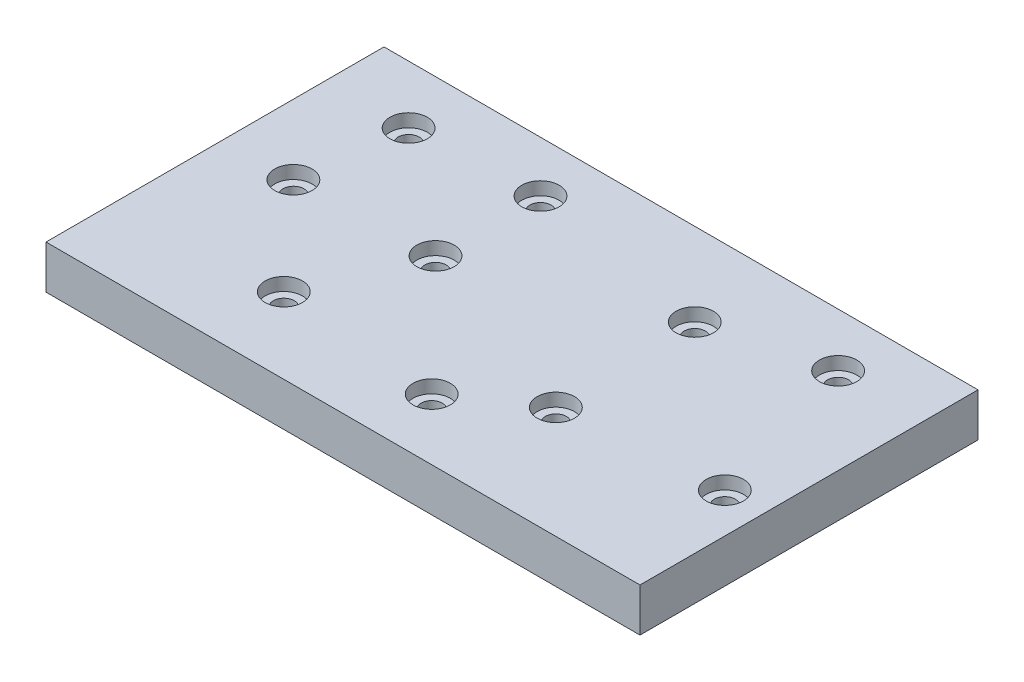
SolidWorks part; units mm, degrees
ref_plane "Front Plane" through (0, 0, 0) normal (0, 0, 1) x (1, 0, 0)
ref_plane "Top Plane" through (0, 0, 0) normal (0, 1, 0) x (1, 0, 0)
ref_plane "Right Plane" through (0, 0, 0) normal (1, 0, 0) x (0, 0, -1)
sketch "Sketch1" plane through (0, 0, 0) normal (0, 1, 0) x (1, 0, 0)
  line L1 (-68.3555, 38.8973) -> (68.3555, 38.8973)
  line L2 (-68.3555, 38.8973) -> (-68.3555, -38.8973)
  line L3 (-68.3555, -38.8973) -> (68.3555, -38.8973)
  line L4 (68.3555, 38.8973) -> (68.3555, -38.8973)
  point P0 (0, 0)
extrude "Boss-Extrude1" add sketch "Sketch1" along normal blind 10
sketch "Sketch2" plane through (0, 10, 0) normal (0, 1, 0) x (1, 0, 0)
  circle A0 centre (-49.3531, 25.5605) radius 2.4163
extrude "Cut-Extrude1" cut sketch "Sketch2" against normal blind 10
sketch "Sketch3" plane through (0, 10, 0) normal (0, 1, 0) x (1, 0, 0)
  circle A0 centre (-49.3531, 25.5605) radius 4.3033
extrude "Cut-Extrude2" cut sketch "Sketch3" against normal blind 3
sketch "Sketch4" plane through (0, 10, 0) normal (0, 1, 0) x (1, 0, 0)
  point P0 (22.2457, 19.8149)
  point P1 (23.277, -13.1854)
  point P2 (-20.6252, 27.181)
  point P3 (-52.2996, 1.9889)
  point P4 (-31.0851, -21.4355)
  point P5 (48.4692, 26.5917)
  point P6 (59.2237, -10.2389)
  point P7 (-20.7725, 3.1674)
  point P8 (6.3349, -24.8239)
pattern_sketch "Sketch-Pattern1" of "Cut-Extrude1", "Cut-Extrude2" driven by "Sketch4"
